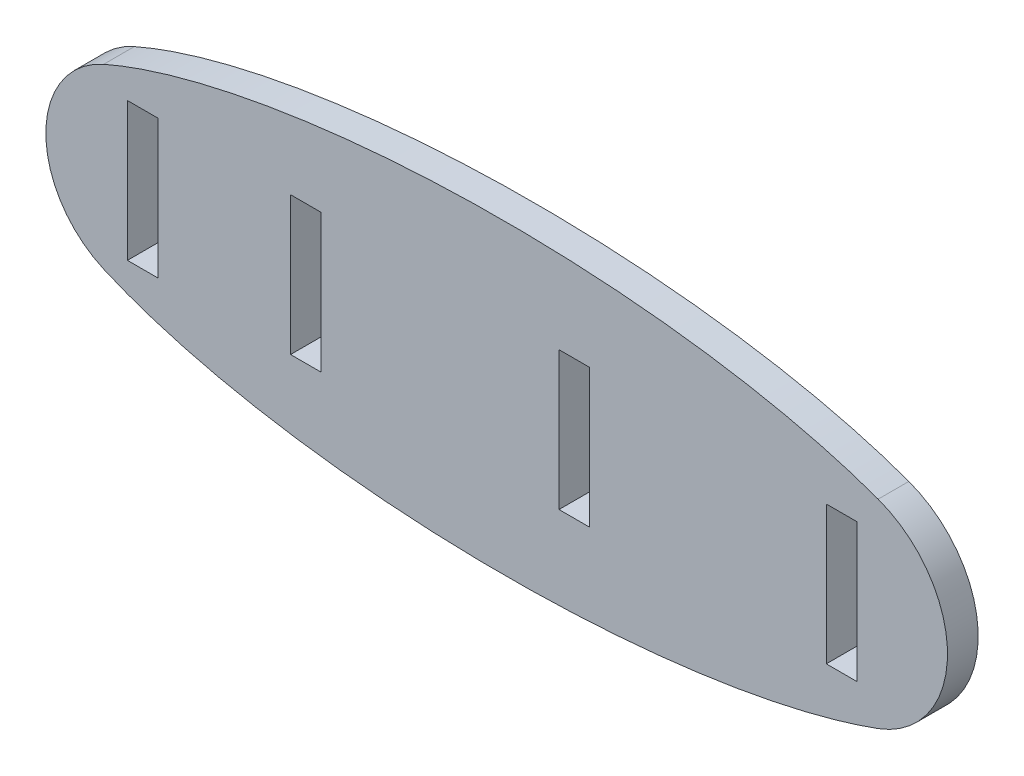
SolidWorks part; units mm, degrees
ref_plane "Front Plane" through (0, 0, 0) normal (0, 0, 1) x (1, 0, 0)
ref_plane "Top Plane" through (0, 0, 0) normal (0, 1, 0) x (1, 0, 0)
ref_plane "Right Plane" through (0, 0, 0) normal (1, 0, 0) x (0, 0, -1)
sketch "Sketch1" plane through (0, 0, 0) normal (0, 0, 1) x (1, 0, 0)
  line L0 (-25.4, 0) -> (25.4, 0) construction
  line L1 (0, 7.9375) -> (0, -7.9375) construction
  line L2 (-11.0524, -3.5814) -> (-9.4649, -3.5814)
  line L3 (-19.4928, -3.5814) -> (-17.9053, -3.5814)
  line L4 (-19.4928, -3.5814) -> (-19.4928, 3.5814)
  line L5 (-19.4928, 3.5814) -> (-17.9053, 3.5814)
  line L6 (-17.9053, -3.5814) -> (-17.9053, 3.5814)
  line L7 (-19.4928, -3.5814) -> (-17.9053, 3.5814) construction
  line L8 (-19.4928, 3.5814) -> (-17.9053, -3.5814) construction
  line L9 (-11.0524, -3.5814) -> (-11.0524, 3.5814)
  line L10 (-11.0524, 3.5814) -> (-9.4649, 3.5814)
  line L11 (-9.4649, -3.5814) -> (-9.4649, 3.5814)
  line L12 (-11.0524, -3.5814) -> (-9.4649, 3.5814) construction
  line L13 (-11.0524, 3.5814) -> (-9.4649, -3.5814) construction
  line L14 (2.8384, -3.5814) -> (4.4259, -3.5814)
  line L15 (2.8384, -3.5814) -> (2.8384, 3.5814)
  line L16 (2.8384, 3.5814) -> (4.4259, 3.5814)
  line L17 (4.4259, -3.5814) -> (4.4259, 3.5814)
  line L18 (2.8384, -3.5814) -> (4.4259, 3.5814) construction
  line L19 (2.8384, 3.5814) -> (4.4259, -3.5814) construction
  line L20 (16.6687, -3.5814) -> (18.2563, -3.5814)
  line L21 (16.6687, -3.5814) -> (16.6687, 3.5814)
  line L22 (16.6687, 3.5814) -> (18.2562, 3.5814)
  line L23 (18.2563, -3.5814) -> (18.2562, 3.5814)
  line L24 (16.6687, -3.5814) -> (18.2562, 3.5814) construction
  line L25 (16.6687, 3.5814) -> (18.2563, -3.5814) construction
  circle A2 centre (-18.6991, 0) radius 5.0162
  circle A3 centre (17.4625, 0) radius 5.4774
  ellipse E0 centre (0, 0) end of major axis (25.4, 0) minor radius 7.9375
  point P15 (-18.6991, 0)
  point P29 (-10.2587, 0)
  point P30 (3.6321, 0)
  point P31 (17.4625, 0)
  point P32 (-18.6991, 3.5814)
  point P33 (-10.2587, 3.5814)
  point P34 (3.6321, 3.5814)
  point P35 (17.4625, 3.5814)
  dimension "D1" = 50.8
  dimension "D2" = 15.875
  dimension "D3" = 7.1628
  dimension "D4" = 8.4404
  dimension "D5" = 13.8908
  dimension "D6" = 13.8304
  dimension "D7" = 1.5875
  dimension "D8" = 7.9375
extrude "Boss-Extrude1" add sketch "Sketch1" along normal blind 1.5875 contours A3 E0 A2 L11 L2 L9 L10 L17 L14 L15 L16 | A2 L6 L3 L4 L5 | A3 L23 L20 L21 L22
fillet "Fillet1" [suppressed] radius 0.4064
